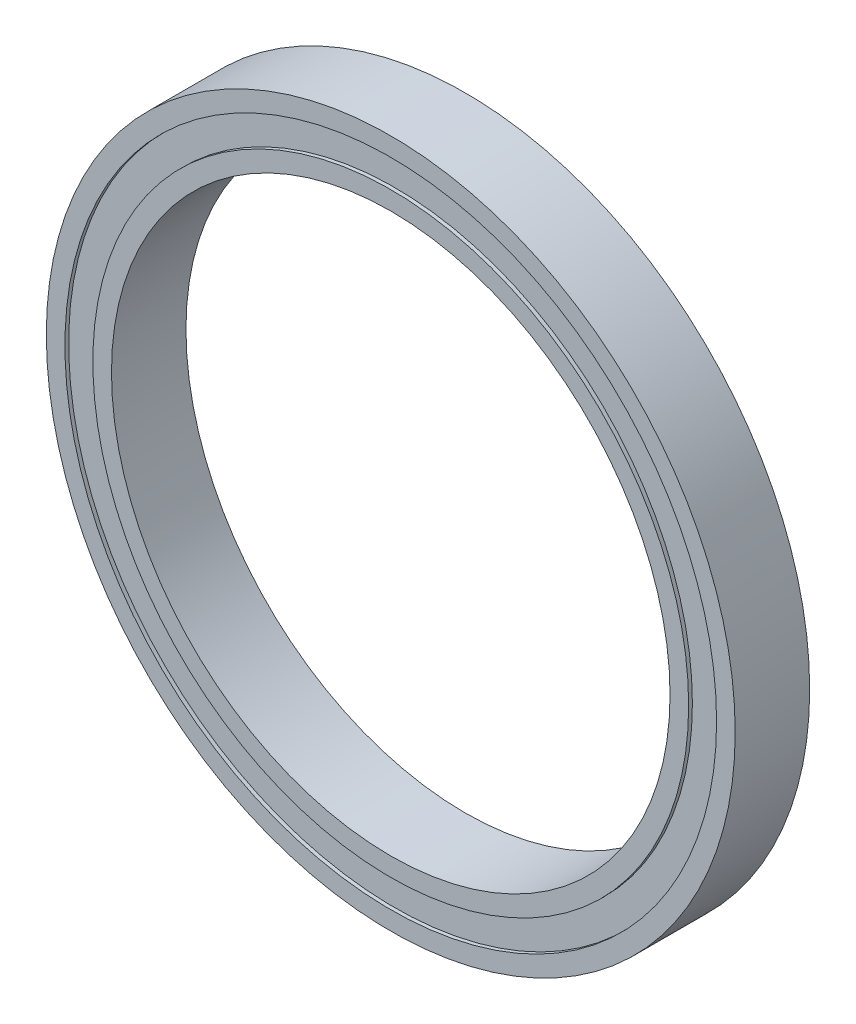
SolidWorks part; units mm, degrees
material "AISI 304"
ref_plane "前视基准面" through (0, 0, 0) normal (0, 0, 1) x (1, 0, 0)
ref_plane "上视基准面" through (0, 0, 0) normal (0, 1, 0) x (1, 0, 0)
ref_plane "右视基准面" through (0, 0, 0) normal (1, 0, 0) x (0, 0, -1)
sketch "草图2" plane through (0, 0, 0) normal (0, 1, 0) x (1, 0, 0)
  line L0 (0, -426.0543) -> (0, 20876.6622) construction
  line L1 (16, 2) -> (16, 1.8)
  line L2 (18.5, -2) -> (17.5, -2)
  line L3 (18.5, -2) -> (18.5, 2)
  line L4 (18.5, 2) -> (17.5, 2)
  line L5 (15, -2) -> (15, 2)
  line L6 (18.5, -2) -> (15, 2) construction
  line L7 (18.5, 2) -> (15, -2) construction
  line L8 (16, 1.8) -> (17.5, 1.8)
  line L9 (17.5, 1.8) -> (17.5, 2)
  line L10 (16, 2) -> (15, 2)
  line L11 (-983.25, 0) -> (49016.75, 0) construction
  line L12 (17.5, -1.8) -> (17.5, -2)
  line L13 (16, -2) -> (16, -1.8)
  line L14 (16, -1.8) -> (17.5, -1.8)
  line L15 (16, -2) -> (15, -2)
  point P1 (16.75, 0)
  dimension "D1" = 37
  dimension "D2" = 4
  dimension "D3" = 30
  dimension "D4" = 1
  dimension "D5" = 1
  dimension "D6" = 0.2
revolve "旋转1" add sketch "草图2" angle 360 about L0
